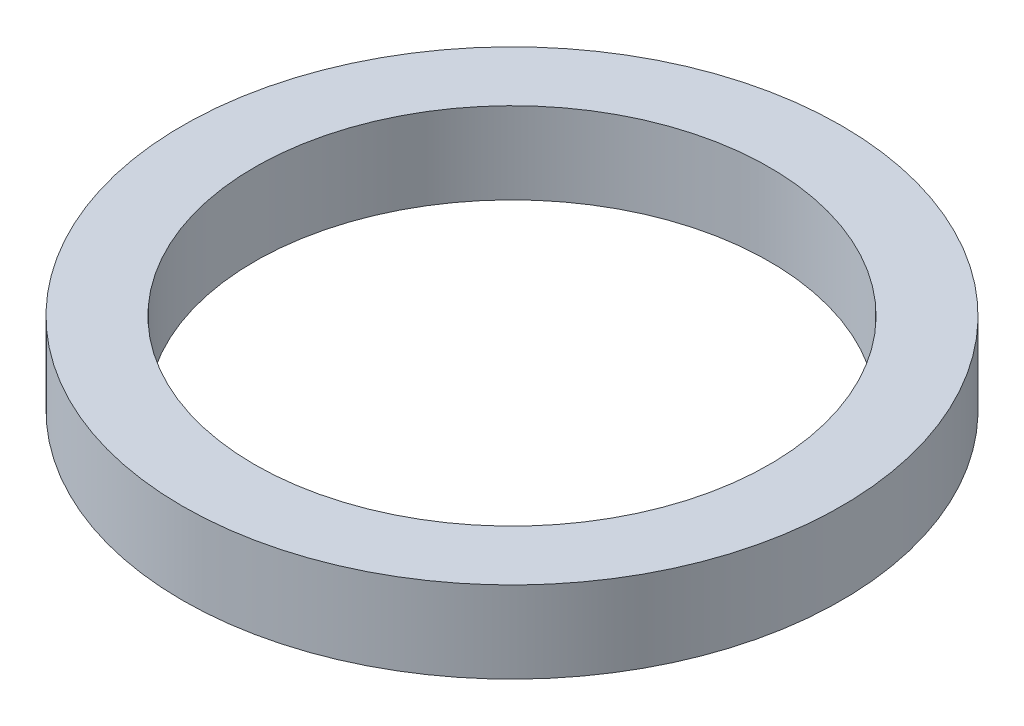
SolidWorks part; units mm, degrees
ref_plane "Front Plane" through (0, 0, 0) normal (0, 0, 1) x (1, 0, 0)
ref_plane "Top Plane" through (0, 0, 0) normal (0, 1, 0) x (1, 0, 0)
ref_plane "Right Plane" through (0, 0, 0) normal (1, 0, 0) x (0, 0, -1)
sketch "Sketch2" plane through (0, 0, 0) normal (0, 1, 0) x (1, 0, 0)
  circle A0 centre (0, 0) radius 12.5
  circle A1 centre (0, 0) radius 16
extrude "Boss-Extrude1" add sketch "Sketch2" along normal blind 3.96
